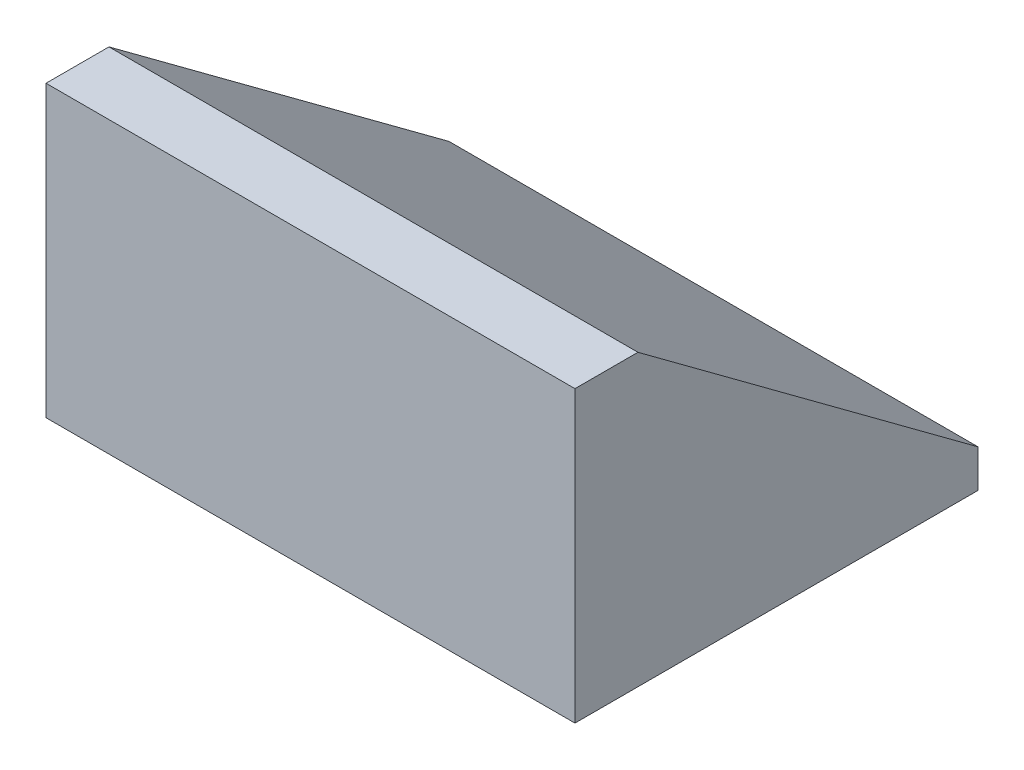
SolidWorks part; units mm, degrees
ref_plane "Front Plane" through (0, 0, 0) normal (0, 0, 1) x (1, 0, 0)
ref_plane "Top Plane" through (0, 0, 0) normal (0, 1, 0) x (1, 0, 0)
ref_plane "Right Plane" through (0, 0, 0) normal (1, 0, 0) x (0, 0, -1)
sketch "Sketch1" plane through (0, 0, 0) normal (0, 0, 1) x (1, 0, 0)
  line L1 (-21, 11.5) -> (21, 11.5)
  line L2 (-21, 11.5) -> (-21, -11.5)
  line L3 (-21, -11.5) -> (21, -11.5)
  line L4 (21, 11.5) -> (21, -11.5)
  line L5 (-21, 11.5) -> (21, -11.5) construction
  line L6 (-21, -11.5) -> (21, 11.5) construction
  point P0 (0, 0)
  point P6 (0, -11.5)
  dimension "D1" = 42
  dimension "D2" = 23
ref_plane "Plane4" through (0, 0, -10) normal (0, 0, 1) x (1, 0, 0)
sketch "Sketch5" plane through (0, 0, -10) normal (0, 0, 1) x (1, 0, 0)
  line L1 (21, 11.5) -> (-21, 11.5)
  line L2 (21, 11.5) -> (21, -11.5)
  line L3 (21, -11.5) -> (-21, -11.5)
  line L4 (-21, 11.5) -> (-21, -11.5)
  line L5 (21, 11.5) -> (-21, -11.5) construction
  line L6 (21, -11.5) -> (-21, 11.5) construction
  point P0 (0, 0)
  dimension "D1" = 42
  dimension "D2" = 23
extrude "Boss-Extrude2" add sketch "Sketch5" against normal blind 32 separate body
sketch "Sketch6" plane through (-21, 0, 0) normal (-1, 0, 0) x (0, 0, 1)
  line L0 (-42, 11.5) -> (-42, -11.5) construction
  line L1 (-42, 11.5) -> (-10, 11.5) construction
  line L3 (-10, -12.65) -> (-10, 12.65) construction
  line L4 (-42, 11.5) -> (-42, -8.5)
  line L5 (-42, -8.5) -> (-15, 11.5)
  line L6 (-15, 11.5) -> (-42, 11.5)
  point P0 (-42, -8.5)
  point P1 (-15, 11.5)
  point P4 (-10, 11.5)
  point P8 (-42, 11.5)
  dimension "D1" = 3
  dimension "D2" = 5
extrude "Cut-Extrude3" cut sketch "Sketch6" against normal blind 42
ref_point "Point2"
ref_plane "Plane5" through (0, -11.5, 0) normal (0, 1, 0) x (1, 0, 0)
sketch "Sketch7" plane through (0, -11.5, 0) normal (0, 1, 0) x (1, 0, 0)
  line L0 (0, 10) -> (0, 0)
  point P4 (0, 5)
ref_point "Point3"
